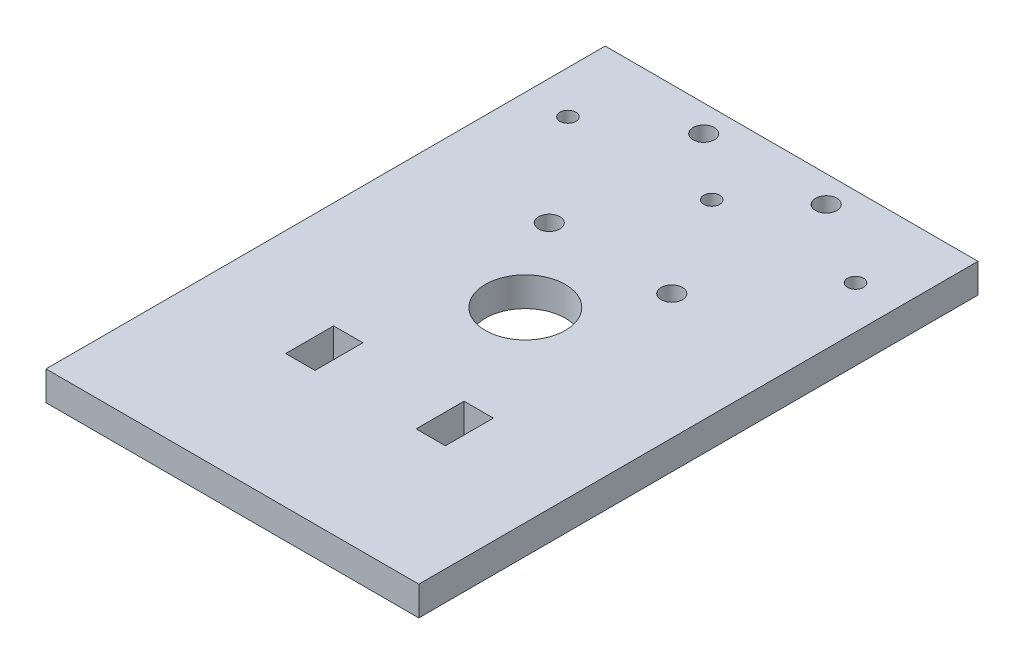
SolidWorks part; units mm, degrees
ref_plane "Alzado" through (0, 0, 0) normal (0, 0, 1) x (1, 0, 0)
ref_plane "Planta" through (0, 0, 0) normal (0, 1, 0) x (1, 0, 0)
ref_plane "Vista lateral" through (0, 0, 0) normal (1, 0, 0) x (0, 0, -1)
sketch "Croquis1" plane through (0, 0, 0) normal (0, 1, 0) x (1, 0, 0)
  line L0 (-106.4065, 6.0772) -> (-36.4065, 6.0772)
  line L1 (-82.9065, 1.0772) -> (-82.9065, -27.9228) construction
  line L2 (-82.9065, 1.0772) -> (-82.9065, 6.0772) construction
  line L3 (-71.4065, 6.0772) -> (-71.4065, -43.9228) construction
  line L4 (-106.4065, 6.0772) -> (-106.4065, -98.9228)
  line L5 (-106.4065, -98.9228) -> (-36.4065, -98.9228)
  line L6 (-36.4065, -98.9228) -> (-36.4065, 6.0772)
  line L8 (-106.4065, -98.9228) -> (-83.6565, -98.9228) construction
  line L9 (-83.6565, -98.9228) -> (-83.6565, -73.9228) construction
  line L10 (-86.4065, -73.9228) -> (-80.9065, -73.9228)
  line L11 (-80.9065, -73.9228) -> (-80.9065, -64.9228)
  line L12 (-80.9065, -64.9228) -> (-86.4065, -64.9228)
  line L13 (-86.4065, -64.9228) -> (-86.4065, -73.9228)
  line L14 (-61.9065, -64.9228) -> (-56.4065, -64.9228)
  line L15 (-56.4065, -64.9228) -> (-56.4065, -73.9228)
  line L16 (-56.4065, -73.9228) -> (-61.9065, -73.9228)
  line L17 (-61.9065, -73.9228) -> (-61.9065, -64.9228)
  circle A0 centre (-82.9065, 1.0772) radius 2
  circle A2 centre (-82.9065, -27.9228) radius 2
  circle A4 centre (-71.4065, -43.9228) radius 7.5
  circle A5 centre (-71.4065, -8.9228) radius 1.5
  circle A6 centre (-59.9065, -27.9228) radius 2
  circle A7 centre (-59.9065, 1.0772) radius 2
  circle A8 centre (-98.4065, -8.9228) radius 1.5
  circle A9 centre (-44.4065, -8.9228) radius 1.5
  dimension "D4" = 4
  dimension "D5" = 23
  dimension "D6" = 4
  dimension "D10" = 15
  dimension "D16" = 3
  dimension "D8" = 3
  dimension "D1" = 70
  dimension "D2" = 5
  dimension "D3" = 29
  dimension "D7" = 105
  dimension "D9" = 50
  dimension "D11" = 22.75
  dimension "D12" = 25
  dimension "D13" = 5.5
  dimension "D14" = 9
  dimension "D15" = 15
extrude "Saliente-Extruir1" add sketch "Croquis1" along normal blind 5.5
